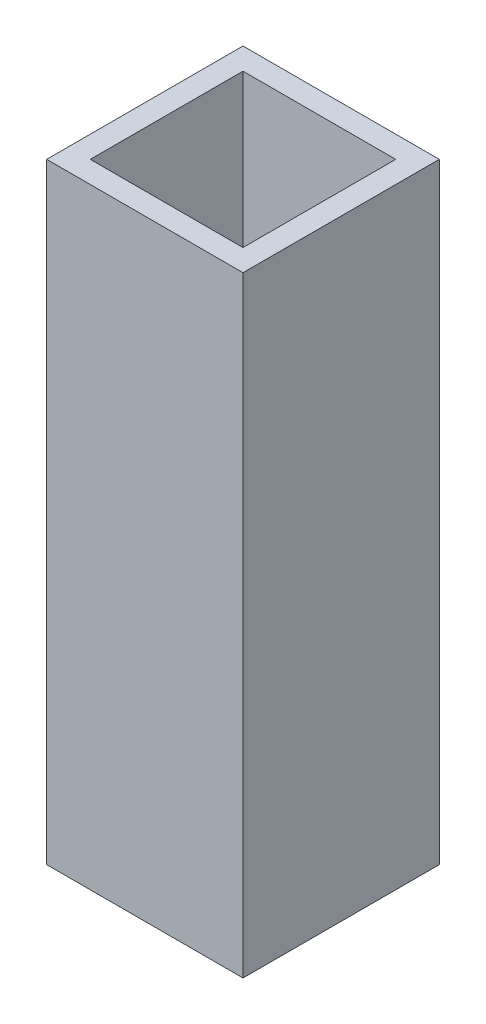
SolidWorks part; units mm, degrees
ref_plane "Alzado" through (0, 0, 0) normal (0, 0, 1) x (1, 0, 0)
ref_plane "Planta" through (0, 0, 0) normal (0, 1, 0) x (1, 0, 0)
ref_plane "Vista lateral" through (0, 0, 0) normal (1, 0, 0) x (0, 0, -1)
sketch "Croquis1" plane through (0, 0, 0) normal (0, 1, 0) x (1, 0, 0)
  line L0 (-5.25, -5.25) -> (-5.25, 5.25)
  line L1 (-6.75, -6.75) -> (6.75, -6.75)
  line L2 (-6.75, -6.75) -> (-6.75, 6.75)
  line L3 (-6.75, 6.75) -> (6.75, 6.75)
  line L4 (6.75, -6.75) -> (6.75, 6.75)
  line L5 (-6.75, -6.75) -> (6.75, 6.75) construction
  line L6 (-6.75, 6.75) -> (6.75, -6.75) construction
  line L7 (-5.25, 5.25) -> (5.25, 5.25)
  line L8 (5.25, -5.25) -> (5.25, 5.25)
  line L9 (-5.25, -5.25) -> (5.25, -5.25)
  point P0 (0, 0)
  dimension "D1" = 13.5
  dimension "D2" = 13.5
  dimension "D3" = 1.5
extrude "Saliente-Extruir1" add sketch "Croquis1" along normal mid plane 42
